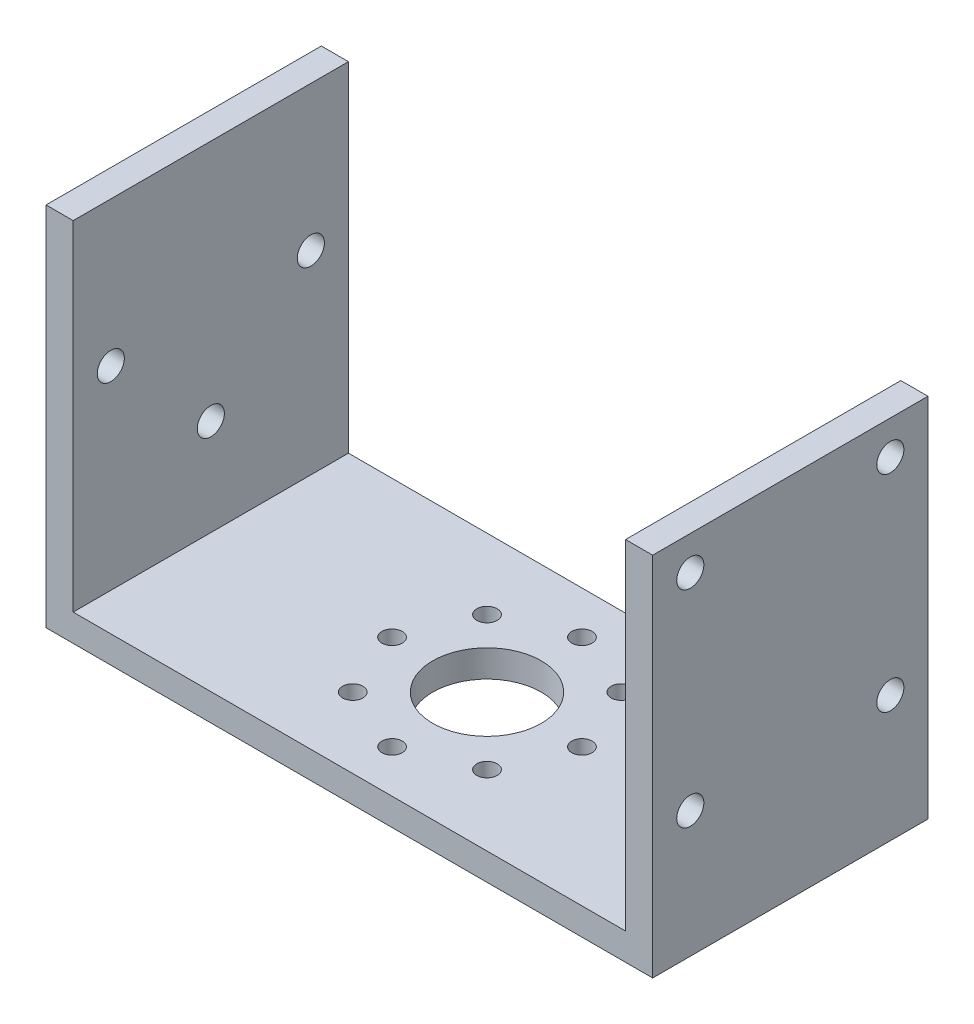
SolidWorks part; units mm, degrees
ref_plane "Front Plane" through (0, 0, 0) normal (0, 0, 1) x (1, 0, 0)
ref_plane "Top Plane" through (0, 0, 0) normal (0, 1, 0) x (1, 0, 0)
ref_plane "Right Plane" through (0, 0, 0) normal (1, 0, 0) x (0, 0, -1)
sketch "Sketch1" plane through (0, 0, 0) normal (0, 1, 0) x (1, 0, 0)
  line L1 (0, 0) -> (44.73, 0)
  line L2 (0, 0) -> (0, 20.3)
  line L3 (0, 20.3) -> (44.73, 20.3)
  line L4 (44.73, 0) -> (44.73, 20.3)
  dimension "D1" = 44.73
  dimension "D2" = 20.3
extrude "YawMount" add sketch "Sketch1" along normal blind 2
sketch "Sketch2" plane through (0, 2, 0) normal (0, 1, 0) x (1, 0, 0)
  line L0 (0, 0) -> (44.73, 0) construction
  line L1 (0, 20.3) -> (2, 20.3)
  line L2 (0, 20.3) -> (0, 0)
  line L3 (0, 0) -> (2, 0)
  line L4 (2, 20.3) -> (2, 0)
  line L6 (44.73, 20.3) -> (42.73, 20.3)
  line L7 (44.73, 20.3) -> (44.73, 0)
  line L8 (44.73, 0) -> (42.73, 0)
  line L9 (42.73, 20.3) -> (42.73, 0)
  dimension "D1" = 2
  dimension "D2" = 2
extrude "BodyConnectors" add sketch "Sketch2" along normal blind 25
sketch "Sketch3" plane through (0, 0, 0) normal (0, -1, 0) x (1, 0, 0)
  line L0 (0, -20.3) -> (0, 0) construction
  line L1 (44.73, -20.3) -> (0, -20.3) construction
  circle A0 centre (22.365, -10.15) radius 4
  point P4 (0, -10.15)
  point P7 (22.365, -20.3)
  dimension "D1" = 8
extrude "Axle-Counterbore" cut sketch "Sketch3" against normal up to surface (2 mm away) up to face at (22.365, 2, -10.15)
sketch "Sketch5" plane through (0, 0, 0) normal (0, -1, 0) x (1, 0, 0)
  line L0 (0, -20.3) -> (0, 0) construction
  line L1 (44.73, -20.3) -> (0, -20.3) construction
  circle A0 centre (15.365, -10.15) radius 0.75
  circle A4 centre (17.4153, -5.2003) radius 0.75
  circle A5 centre (22.365, -3.15) radius 0.75
  circle A6 centre (27.3147, -5.2003) radius 0.75
  circle A7 centre (29.365, -10.15) radius 0.75
  circle A8 centre (27.3147, -15.0997) radius 0.75
  circle A9 centre (22.365, -17.15) radius 0.75
  circle A10 centre (17.4153, -15.0997) radius 0.75
  point P6 (0, -10.15)
  point P24 (22.365, -10.15)
  point P25 (22.365, -20.3)
  dimension "D1" = 1.5
  dimension "D2" = 7
  dimension "D3" = 8
extrude "azel-mountscrews" cut sketch "Sketch5" against normal up to surface (2 mm away) up to face at (22.365, 2, -14.15)
sketch "Sketch6" plane through (2, 0, 0) normal (1, 0, 0) x (0, 0, -1)
  line L0 (0, 27) -> (20.3, 27) construction
  line L3 (0, 2) -> (20.3, 2) construction
  circle A1 centre (10.15, 9.12) radius 1
  circle A2 centre (17.525, 16.33) radius 1
  circle A3 centre (2.775, 16.33) radius 1
  point P5 (10.15, 27)
  dimension "D2" = 2
  dimension "D3" = 14.75
  dimension "D4" = 7.21
  dimension "D5" = 7.375
  dimension "D1" = 7.12
extrude "GearSide-Screws" cut sketch "Sketch6" against normal up to surface (2 mm away) up to face at (0, 13.5, -10.15)
sketch "Sketch7" plane through (42.73, 0, 0) normal (-1, 0, 0) x (0, 0, 1)
  line L0 (-20.3, 2) -> (0, 2) construction
  circle A0 centre (-2.775, 9.3) radius 1
  circle A1 centre (-17.525, 9.3) radius 1
  circle A2 centre (-17.525, 24.5) radius 1
  circle A3 centre (-2.775, 24.5) radius 1
  point P14 (-10.15, 2)
  dimension "D2" = 2
  dimension "D3" = 14.75
  dimension "D1" = 7.3
  dimension "D4" = 7.375
  dimension "D5" = 15.2
extrude "SmoothSide-Screws" cut sketch "Sketch7" against normal up to surface (2 mm away) up to face at (44.73, 13.5, -10.15)
equation "\"srv_w\"= 40.43mm'width of Sain Smart SR319"
equation "\"D1@Sketch1\"=\"srv_w\" + \"mnt_thick\"*2.15"
equation "\"srv_h\"= 40.61mm'height of Sain Smart SR319"
equation "\"srv_d\"= 20.3mm'depth of Sain Smart SR319"
equation "\"D2@Sketch1\"=\"srv_d\""
equation "\"mnt_thick\"= 2mm'thickness of bracket"
equation "\"D1@YawMount\" = \"mnt_thick\""
equation "\"D2@Sketch2\"=\"mnt_thick\""
equation "\"D1@Sketch2\"=\"mnt_thick\""
equation "\"D5@Sketch6\"=\"D3@Sketch6\"/2"
equation "\"D4@Sketch7\"=\"D3@Sketch7\"/2"
equation "\"clearance\"= 5mm'extra space between bracket and roll rotator servo"
equation "\"D1@Sketch6\"=\"clearance\"+2.12mm"
equation "\"D1@Sketch7\"=\"clearance\"+2.3mm"
equation "\"D1@BodyConnectors\"=20+\"clearance\""
